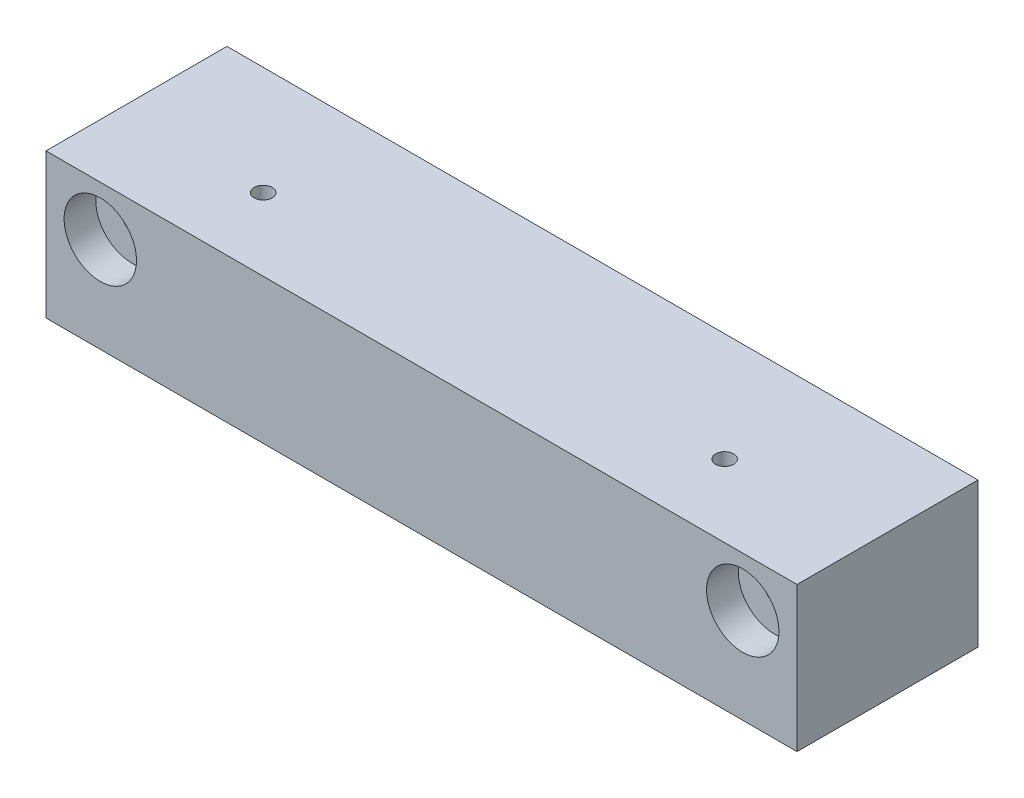
SolidWorks part; units mm, degrees
ref_plane "정면" through (0, 0, 0) normal (0, 0, 1) x (1, 0, 0)
ref_plane "윗면" through (0, 0, 0) normal (0, 1, 0) x (1, 0, 0)
ref_plane "우측면" through (0, 0, 0) normal (1, 0, 0) x (0, 0, -1)
sketch "스케치1" plane through (0, 0, 0) normal (0, 1, 0) x (1, 0, 0)
  line L1 (-41.5, 10) -> (41.5, 10)
  line L2 (-41.5, 10) -> (-41.5, -10)
  line L3 (-41.5, -10) -> (41.5, -10)
  line L4 (41.5, 10) -> (41.5, -10)
  line L5 (-41.5, 10) -> (41.5, -10) construction
  line L6 (-41.5, -10) -> (41.5, 10) construction
  point P0 (0, 0)
  dimension "D1" = 83
  dimension "D2" = 20
extrude "보스-돌출1" add sketch "스케치1" along normal blind 16
sketch "스케치2" plane through (0, 0, 10) normal (0, 0, 1) x (1, 0, 0)
  line L3 (-41.5, 16) -> (41.5, 16) construction
  line L4 (-41.5, 16) -> (-41.5, 0) construction
  line L6 (41.5, 16) -> (41.5, 0) construction
  circle A2 centre (-35.5, 10.5) radius 4
  circle A3 centre (35.5, 10.5) radius 4
  dimension "D1" = 8
  dimension "D2" = 8
  dimension "D4" = 5.5
  dimension "D5" = 6
  dimension "D6" = 6
extrude "컷-돌출1" cut sketch "스케치2" against normal blind 3.5
sketch "스케치3" plane through (0, 16, 0) normal (0, 1, 0) x (1, 0, 0)
  line L0 (-41.5, 10) -> (-41.5, -10) construction
  line L1 (-41.5, -10) -> (41.5, -10) construction
  line L2 (41.5, -10) -> (41.5, 10) construction
  circle A0 centre (-25.5, -2) radius 1
  circle A1 centre (25.5, -2) radius 1
  dimension "D1" = 2
  dimension "D2" = 16
  dimension "D3" = 8
  dimension "D4" = 16
  dimension "D5" = 8
extrude "컷-돌출2" cut sketch "스케치3" against normal blind 10
sketch "스케치6" plane through (0, 0, 6.5) normal (0, 0, 1) x (1, 0, 0)
  circle A0 centre (-35.5, 10.5) radius 1
  circle A1 centre (35.5, 10.5) radius 1
  dimension "D1" = 2
extrude "컷-돌출5" cut sketch "스케치6" against normal blind 8
